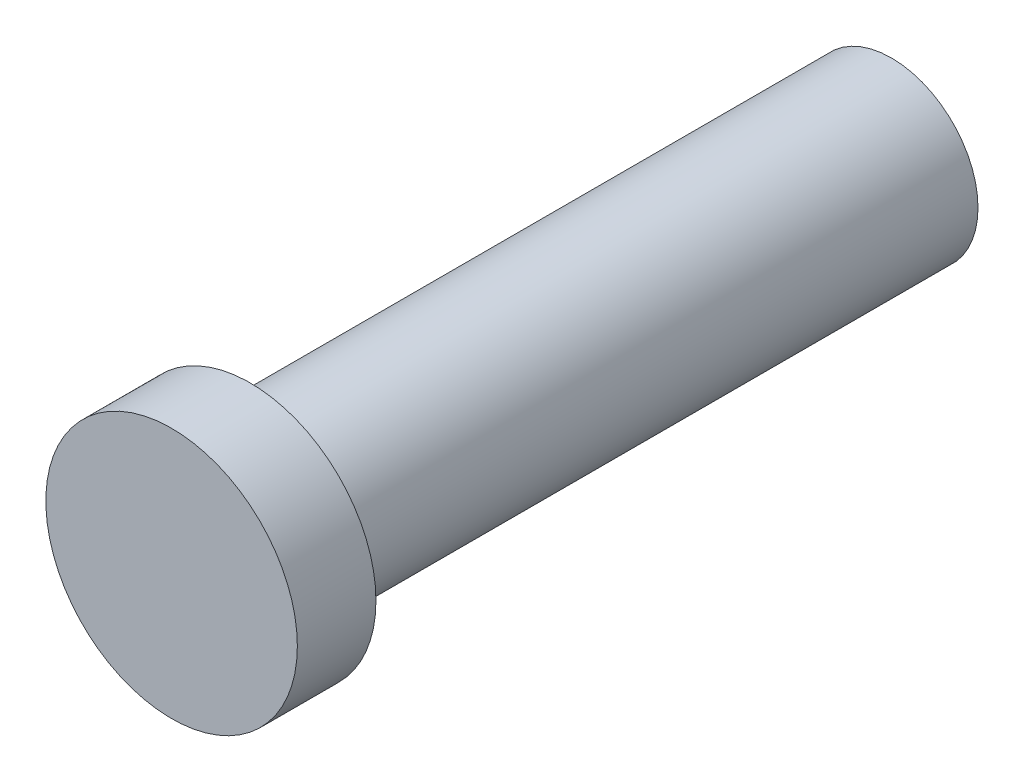
SolidWorks part; units mm, degrees
ref_plane "Front Plane" through (0, 0, 0) normal (0, 0, 1) x (1, 0, 0)
ref_plane "Top Plane" through (0, 0, 0) normal (0, 1, 0) x (1, 0, 0)
ref_plane "Right Plane" through (0, 0, 0) normal (1, 0, 0) x (0, 0, -1)
sketch "Sketch1" plane through (0, 0, 0) normal (0, 0, 1) x (1, 0, 0)
  circle A1 centre (0, 0) radius 5.5
  dimension "D1" = 11
extrude "Boss-Extrude1" add sketch "Sketch1" along normal blind 40.8
sketch "Sketch2" plane through (0, 0, 40.8) normal (0, 0, 1) x (1, 0, 0)
  circle A0 centre (0, 0) radius 8
  dimension "D1" = 16
extrude "Boss-Extrude2" add sketch "Sketch2" along normal blind 5 contours A0
sketch "Sketch3" plane through (0, 0, 0) normal (0, 0, -1) x (-1, 0, 0)
  circle A0 centre (0, 0) radius 3.8
  dimension "D1" = 7.6
extrude "Cut-Extrude1" cut sketch "Sketch3" against normal blind 40
